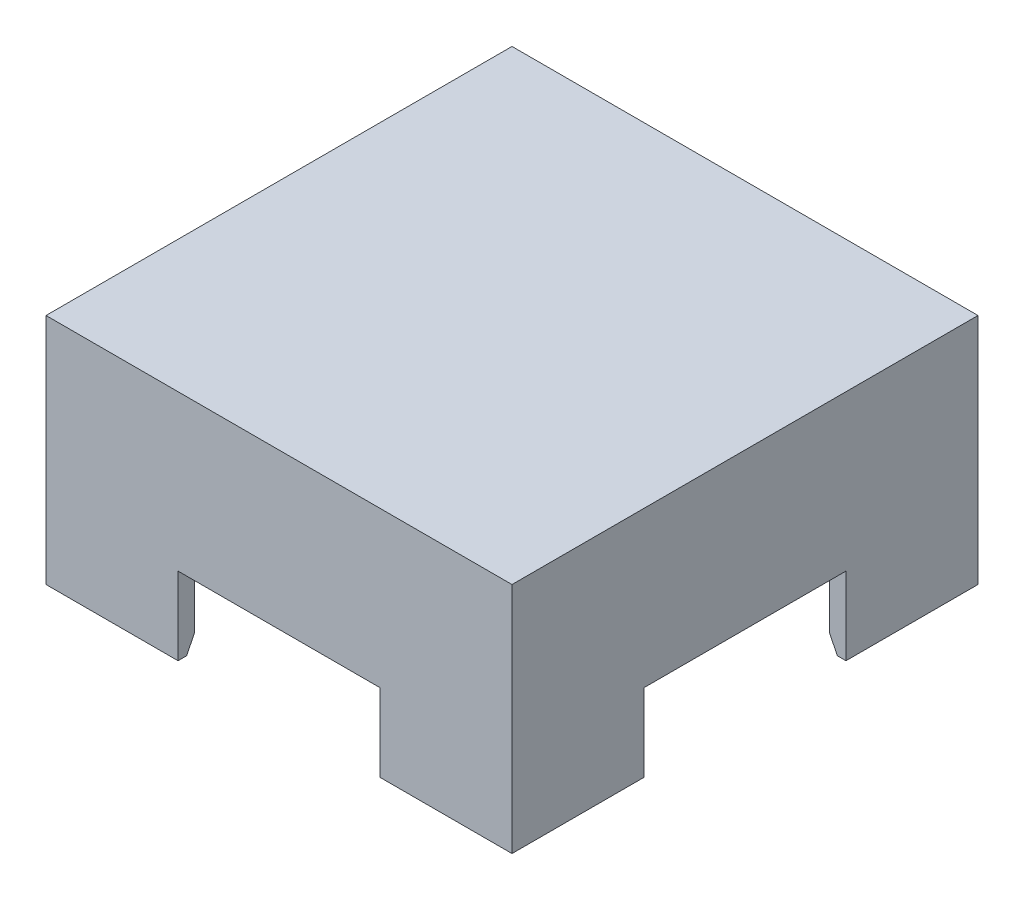
SolidWorks part; units mm, degrees
ref_plane "Front Plane" through (0, 0, 0) normal (0, 0, 1) x (1, 0, 0)
ref_plane "Top Plane" through (0, 0, 0) normal (0, 1, 0) x (1, 0, 0)
ref_plane "Right Plane" through (0, 0, 0) normal (1, 0, 0) x (0, 0, -1)
sketch "Sketch1" plane through (0, 1478.6171, 0) normal (0, 1, 0) x (1, 0, 0)
  line L1 (-530.1492, -768.8296) -> (-453.9492, -768.8296)
  line L2 (-530.1492, -768.8296) -> (-530.1492, -845.0296)
  line L3 (-530.1492, -845.0296) -> (-453.9492, -845.0296)
  line L4 (-453.9492, -768.8296) -> (-453.9492, -845.0296)
  line L5 (-530.1492, -768.8296) -> (-453.9492, -845.0296) construction
  line L6 (-530.1492, -845.0296) -> (-453.9492, -768.8296) construction
  point P0 (-492.0492, -806.9296)
  dimension "D1" = 76.2
  dimension "D2" = 76.2
extrude "Boss-Extrude1" add sketch "Sketch1" along normal blind 25.4
sketch "Sketch2" plane through (0, 1478.6171, 0) normal (0, -1, 0) x (-1, 0, 0)
  line L1 (463.4742, -778.3546) -> (520.6242, -778.3546)
  line L2 (463.4742, -778.3546) -> (463.4742, -835.5046)
  line L3 (463.4742, -835.5046) -> (520.6242, -835.5046)
  line L4 (520.6242, -778.3546) -> (520.6242, -835.5046)
  line L5 (463.4742, -778.3546) -> (520.6242, -835.5046) construction
  line L6 (463.4742, -835.5046) -> (520.6242, -778.3546) construction
  point P0 (492.0492, -806.9296)
  dimension "D1" = 57.15
  dimension "D2" = 57.15
extrude "Cut-Extrude1" cut sketch "Sketch2" against normal blind 19.05
sketch "Sketch3" plane through (0, 1478.6171, 0) normal (0, -1, 0) x (-1, 0, 0)
  line L0 (530.1492, -768.8296) -> (530.1492, -845.0296) construction
  line L1 (530.1492, -790.4196) -> (527.4822, -790.4196)
  line L3 (530.1492, -823.4396) -> (527.4822, -823.4396)
  line L5 (453.9492, -768.8296) -> (530.1492, -768.8296) construction
  line L7 (508.5592, -768.8296) -> (508.5592, -771.4966)
  line L9 (475.5392, -768.8296) -> (475.5392, -771.4966)
  line L10 (530.1492, -845.0296) -> (453.9492, -845.0296) construction
  line L12 (508.5592, -845.0296) -> (508.5592, -842.3626)
  line L14 (475.5392, -845.0296) -> (475.5392, -842.3626)
  line L15 (453.9492, -845.0296) -> (453.9492, -768.8296) construction
  line L16 (453.9492, -823.4396) -> (456.6162, -823.4396)
  line L18 (453.9492, -790.4196) -> (456.6162, -790.4196)
  line L24 (530.1492, -790.4196) -> (530.1492, -768.8296)
  line L25 (530.1492, -768.8296) -> (508.5592, -768.8296)
  line L26 (508.5592, -771.4966) -> (527.4822, -771.4966)
  line L27 (527.4822, -771.4966) -> (527.4822, -790.4196)
  line L28 (530.1492, -823.4396) -> (530.1492, -845.0296)
  line L29 (530.1492, -845.0296) -> (508.5592, -845.0296)
  line L30 (508.5592, -842.3626) -> (527.4822, -842.3626)
  line L31 (527.4822, -842.3626) -> (527.4822, -823.4396)
  line L32 (475.5392, -845.0296) -> (453.9492, -845.0296)
  line L33 (453.9492, -845.0296) -> (453.9492, -823.4396)
  line L34 (475.5392, -842.3626) -> (456.6162, -842.3626)
  line L35 (456.6162, -842.3626) -> (456.6162, -823.4396)
  line L36 (453.9492, -790.4196) -> (453.9492, -768.8296)
  line L37 (453.9492, -768.8296) -> (475.5392, -768.8296)
  line L38 (475.5392, -771.4966) -> (456.6162, -771.4966)
  line L39 (456.6162, -771.4966) -> (456.6162, -790.4196)
  dimension "D1" = 21.59
  dimension "D2" = 21.59
  dimension "D3" = 21.59
  dimension "D4" = 21.59
  dimension "D5" = 21.59
  dimension "D6" = 21.59
  dimension "D7" = 21.59
  dimension "D8" = 21.59
extrude "Boss-Extrude2" add sketch "Sketch3" along normal blind 12.7
chamfer "Chamfer1" distance 2.54 distance2 1.27 8 edges at (-518.0207, 1465.9171, 771.4966) (-527.4822, 1465.9171, 780.9581) (-527.4822, 1465.9171, 832.9011) (-518.0207, 1465.9171, 842.3626) (-466.0777, 1465.9171, 771.4966) (-456.6162, 1465.9171, 780.9581) (-466.0777, 1465.9171, 842.3626) (-456.6162, 1465.9171, 832.9011)
